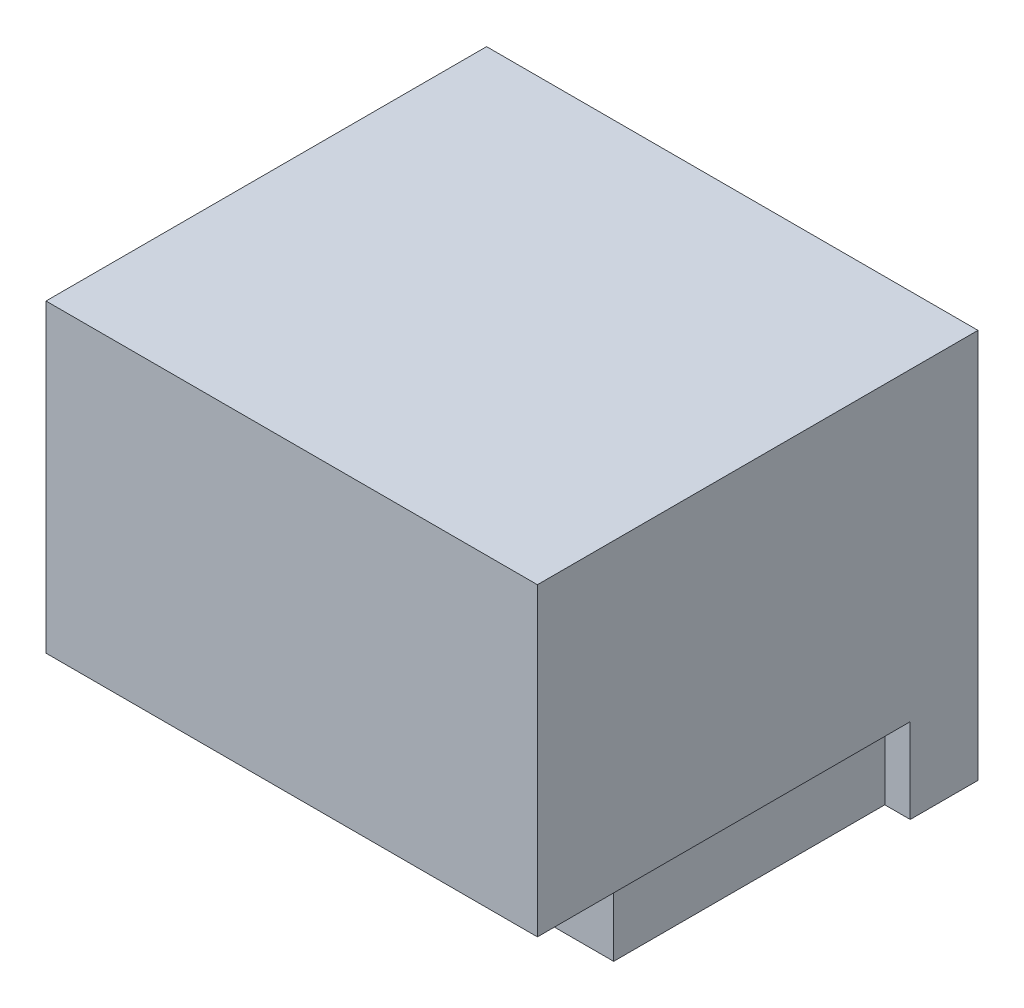
SolidWorks part; units mm, degrees
ref_plane "前视基准面" through (0, 0, 0) normal (0, 0, 1) x (1, 0, 0)
ref_plane "上视基准面" through (0, 0, 0) normal (0, 1, 0) x (1, 0, 0)
ref_plane "右视基准面" through (0, 0, 0) normal (1, 0, 0) x (0, 0, -1)
sketch "草图1" plane through (0, 0, 0) normal (0, 1, 0) x (1, 0, 0)
  line L1 (-5.7358, 5.5063) -> (8.7642, 5.5063)
  line L2 (-5.7358, 5.5063) -> (-5.7358, -7.4937)
  line L3 (-5.7358, -7.4937) -> (8.7642, -7.4937)
  line L4 (8.7642, 5.5063) -> (8.7642, -7.4937)
  line L5 (-5.7358, 5.5063) -> (8.7642, -7.4937) construction
  line L6 (-5.7358, -7.4937) -> (8.7642, 5.5063) construction
  point P4 (1.5142, -0.9937)
  dimension "D1" = 14.5
  dimension "D2" = 13
extrude "凸台-拉伸1" add sketch "草图1" along normal blind 9
sketch "草图2" plane through (0, 0, 0) normal (0, -1, 0) x (1, 0, 0)
  line L0 (8.7642, -5.5063) -> (-5.7358, -5.5063) construction
  line L1 (-5.7358, -3.5063) -> (8.7642, -3.5063) construction
  line L2 (-5.7358, -3.5063) -> (-5.7358, -5.5063)
  line L3 (-5.7358, -5.5063) -> (8.7642, -5.5063)
  line L4 (8.7642, -3.5063) -> (8.7642, -5.5063)
  line L5 (-5.7358, -3.5063) -> (8.7642, -5.5063) construction
  line L6 (-5.7358, -5.5063) -> (8.7642, -3.5063) construction
  line L7 (-5.7358, -3.5063) -> (-4.9858, -3.5063)
  line L8 (-4.9858, 4.4937) -> (8.0142, 4.4937)
  line L9 (-4.9858, 4.4937) -> (-4.9858, -3.5063)
  line L11 (8.0142, 4.4937) -> (8.0142, -3.5063)
  line L12 (-4.9858, 4.4937) -> (8.0142, -3.5063) construction
  line L13 (-4.9858, -3.5063) -> (8.0142, 4.4937) construction
  line L14 (8.0142, -3.5063) -> (8.7642, -3.5063)
  point P4 (1.5142, -4.5063)
  point P5 (1.5142, -5.5063)
  point P13 (1.5142, 0.4937)
  dimension "D1" = 14.5
  dimension "D2" = 2
  dimension "D3" = 13
  dimension "D4" = 8
extrude "凸台-拉伸2" add sketch "草图2" along normal blind 2.5
sketch "草图3" plane through (0, 0, -5.5063) normal (0, 0, -1) x (-1, 0, 0)
  line L0 (-8.7642, 9) -> (5.7358, 9) construction
  line L1 (-7.5142, 7) -> (4.4858, 7)
  line L2 (-7.5142, 7) -> (-7.5142, 0)
  line L3 (-7.5142, 0) -> (4.4858, 0)
  line L4 (4.4858, 7) -> (4.4858, 0)
  line L5 (-7.5142, 7) -> (4.4858, 0) construction
  line L6 (-7.5142, 0) -> (4.4858, 7) construction
  point P4 (-1.5142, 3.5)
  point P5 (-1.5142, 9)
  point P6 (0, 0)
  dimension "D1" = 12
  dimension "D2" = 7
  dimension "D3" = 2
extrude "切除-拉伸1" cut sketch "草图3" against normal blind 9.7
sketch "草图4" plane through (0, 0, -5.5063) normal (0, 0, -1) x (-1, 0, 0)
  line L0 (-7.5142, 0) -> (4.4858, 0) construction
  line L1 (-4.5142, 0) -> (1.4858, 0)
  line L2 (-4.5142, 0) -> (-4.5142, -1.5)
  line L4 (1.4858, 0) -> (1.4858, -1.5)
  line L5 (-4.5142, 0) -> (1.4858, -1.5) construction
  line L6 (-4.5142, -1.5) -> (1.4858, 0) construction
  line L7 (-7.5142, 0) -> (4.4858, 0) construction
  line L8 (5.7358, -2.5) -> (-8.7642, -2.5) construction
  line L10 (-3.2642, -1.5) -> (-3.2642, -2.5)
  line L11 (-3.2642, -2.5) -> (0.2358, -2.5)
  line L12 (0.2358, -1.5) -> (0.2358, -2.5)
  line L13 (-3.2642, -1.5) -> (0.2358, -2.5) construction
  line L14 (-3.2642, -2.5) -> (0.2358, -1.5) construction
  line L15 (-4.5142, -1.5) -> (-3.2642, -1.5)
  line L16 (0.2358, -1.5) -> (1.4858, -1.5)
  point P4 (-1.5142, -0.75)
  point P5 (-1.5142, 0)
  point P14 (-1.5142, -2)
  dimension "D1" = 6
  dimension "D2" = 1.5
  dimension "D3" = 3.5
extrude "切除-拉伸2" cut sketch "草图4" against normal blind 6.5
sketch "草图5" plane through (0, -2.5, 0) normal (0, -1, 0) x (1, 0, 0)
  line L0 (-4.4858, -5.5063) -> (7.5142, -5.5063) construction
  line L1 (-2.2471, 0.9937) -> (5.2756, 0.9937)
  line L2 (-2.2471, 0.9937) -> (-2.2471, -4.0063)
  line L3 (-2.2471, -4.0063) -> (5.2756, -4.0063)
  line L4 (5.2756, 0.9937) -> (5.2756, -4.0063)
  line L5 (-2.2471, 0.9937) -> (5.2756, -4.0063) construction
  line L6 (-2.2471, -4.0063) -> (5.2756, 0.9937) construction
  line L7 (-5.7358, -5.5063) -> (-0.2358, -5.5063) construction
  line L8 (3.2642, 0.9937) -> (-0.2358, 0.9937) construction
  point P4 (1.5142, -1.5063)
  point P5 (0, 0)
  point P7 (1.5142, -5.5063)
  dimension "D1" = 1.5
extrude "切除-拉伸3" cut sketch "草图5" against normal blind 6.5
sketch "草图6" plane through (0, -2.5, 0) normal (0, -1, 0) x (1, 0, 0)
  line L1 (-4.1158, 3.6246) -> (-3.1158, 3.6246)
  line L2 (-4.1158, 3.6246) -> (-4.1158, -4.3754)
  line L3 (-4.1158, -4.3754) -> (-3.1158, -4.3754)
  line L4 (-3.1158, 3.6246) -> (-3.1158, -4.3754)
  line L5 (-4.1158, 3.6246) -> (-3.1158, -4.3754) construction
  line L6 (-4.1158, -4.3754) -> (-3.1158, 3.6246) construction
  line L7 (6.1442, 3.6246) -> (7.1442, 3.6246)
  line L8 (6.1442, 3.6246) -> (6.1442, -4.3754)
  line L9 (6.1442, -4.3754) -> (7.1442, -4.3754)
  line L10 (7.1442, 3.6246) -> (7.1442, -4.3754)
  line L11 (6.1442, 3.6246) -> (7.1442, -4.3754) construction
  line L12 (6.1442, -4.3754) -> (7.1442, 3.6246) construction
  line L14 (-4.9858, 4.4937) -> (-4.9858, -3.5063) construction
  line L15 (8.0142, -3.5063) -> (8.0142, 4.4937) construction
  point P4 (-3.6158, -0.3754)
  point P9 (6.6442, -0.3754)
  point P10 (0, 0)
  point P14 (0, 0)
  point P15 (0, 0)
  point P16 (-3.4337, -0.3754)
  point P17 (-4.184, 0.9937)
  point P18 (0, 0)
  point P19 (-4.3488, 0.9937)
  point P20 (0, 0)
  point P21 (0, 0)
  point P22 (0, 0)
  dimension "D1" = 1
  dimension "D2" = 8
  dimension "D3" = 1
  dimension "D4" = 8
  dimension "D5" = 1.37
  dimension "D6" = 1.37
extrude "切除-拉伸4" cut sketch "草图6" against normal blind 1
